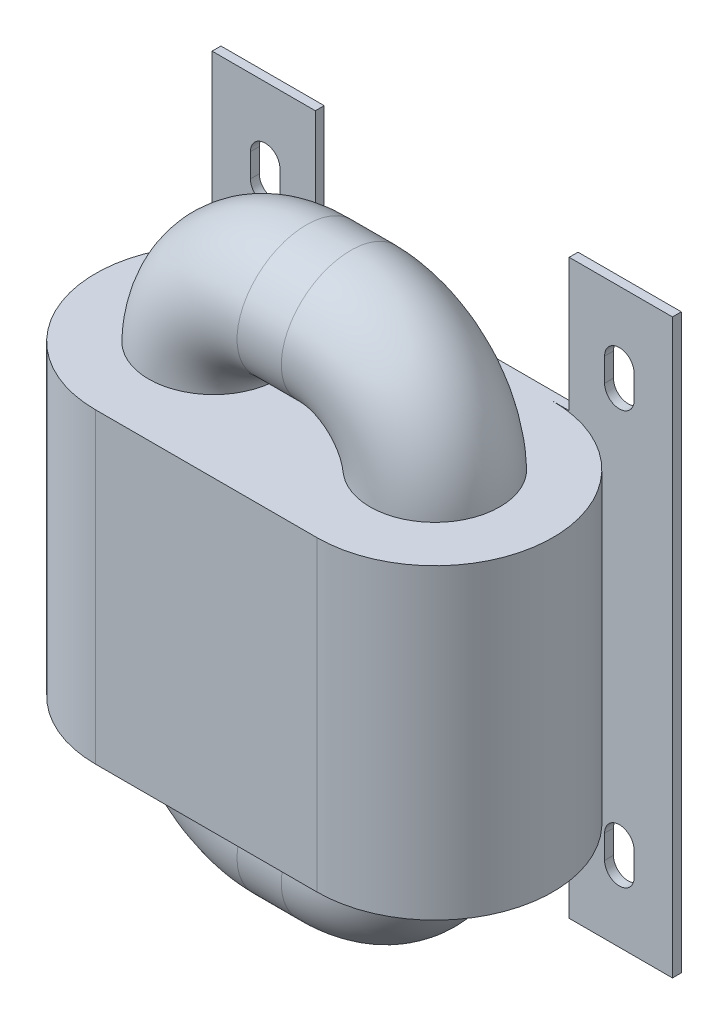
SolidWorks part; units mm, degrees
ref_plane "前视" through (0, 0, 0) normal (0, 0, 1) x (1, 0, 0)
ref_plane "上视" through (0, 0, 0) normal (0, 1, 0) x (1, 0, 0)
ref_plane "右视" through (0, 0, 0) normal (1, 0, 0) x (0, 0, -1)
sketch "草图1" plane through (0, 0, 0) normal (0, 1, 0) x (1, 0, 0)
  line L0 (0, 88.1369) -> (0, -92.5338) construction
  line L1 (-127.3089, 0) -> (111.3203, 0) construction
  line L2 (-18.75, 20) -> (18.75, 20)
  line L3 (-18.75, -20) -> (18.75, -20)
  arc A0 (-18.75, 20) -> (-18.75, -20) centre (-18.75, 0) ccw
  arc A1 (18.75, 20) -> (18.75, -20) centre (18.75, 0) cw
  dimension "D1" = 40
  dimension "D3" = 40
  dimension "D2" = 37.5
extrude "拉伸1" add sketch "草图1" along normal blind 52
sketch "草图2" plane through (0, 0, -20) normal (0, 0, -1) x (-1, 0, 0)
  line L0 (0, -24.0953) -> (0, 77.1566) construction
  line L1 (-65.697, 26) -> (66.5461, 26) construction
  line L2 (-18.75, 0) -> (18.75, 0) construction
  line L3 (39, 74.5) -> (39, -22.5)
  line L5 (-39, 74.5) -> (-39, -22.5)
  line L7 (-39, 74.5) -> (-21.5, 74.5)
  line L8 (-39, -22.5) -> (-21.5, -22.5)
  line L9 (-21.5, 0) -> (21.5, 0)
  line L10 (18.75, 0) -> (38.75, 0) construction
  line L11 (-21.5, 0) -> (-21.5, -22.5)
  line L12 (21.5, 0) -> (21.5, -22.5)
  line L13 (21.5, -22.5) -> (39, -22.5)
  line L14 (21.5, 52) -> (21.5, 74.5)
  line L15 (-21.5, 52) -> (-21.5, 74.5)
  line L16 (-21.5, 52) -> (21.5, 52)
  line L17 (21.5, 74.5) -> (39, 74.5)
  dimension "D1" = 26
  dimension "D2" = 97
  dimension "D3" = 78
  dimension "D4" = 43
extrude "拉伸2" add sketch "草图2" along normal blind 1.5
ref_plane "基准面1" through (0, 0, 0) normal (0, 0, 1) x (1, 0, 0)
sketch "草图3" plane through (0, 0, 0) normal (0, 0, 1) x (1, 0, 0)
  line L0 (0, 76.9957) -> (0, -34.1881) construction
  line L1 (18.75, 51) -> (18.75, 5)
  line L2 (-66.0355, 26) -> (65.5486, 26) construction
  line L3 (-18.75, 52) -> (18.75, 52) construction
  line L4 (-18.75, 51) -> (-18.75, 5)
  line L5 (-3.75, 66) -> (3.75, 66)
  line L6 (-3.75, -10) -> (3.75, -10)
  arc A0 (18.75, 51) -> (3.75, 66) centre (3.75, 51) ccw
  arc A1 (-18.75, 51) -> (-3.75, 66) centre (-3.75, 51) cw
  arc A2 (3.75, -10) -> (18.75, 5) centre (3.75, 5) ccw
  arc A3 (-3.75, -10) -> (-18.75, 5) centre (-3.75, 5) cw
  point P14 (18.75, 66)
  point P17 (-18.75, 66)
  point P20 (18.75, -10)
  point P23 (-18.75, -10)
  dimension "D5" = 15
  dimension "D6" = 15
  dimension "D1" = 76
  dimension "D2" = 26
  dimension "D3" = 40
  dimension "D4" = 37.5
sketch "草图4" plane through (0, 52, 0) normal (0, 1, 0) x (-1, 0, 0)
  circle A0 centre (-18.75, 0) radius 11
  dimension "D1" = 22
sweep "扫描4" add profiles "草图4" path "草图3"
sketch "草图6" plane through (0, 0, -21.5) normal (0, 0, -1) x (-1, 0, 0)
  line L0 (0, -25.2034) -> (0, 83.8054) construction
  line L2 (39, 26) -> (-39, 26) construction
  line L3 (39, -22.5) -> (39, 74.5) construction
  line L4 (-39, 74.5) -> (-39, -22.5) construction
  line L5 (-44.8519, 63) -> (54.6042, 63) construction
  line L6 (-44.8519, 59) -> (54.6042, 59) construction
  line L7 (-32.5, 63) -> (-32.5, 59)
  line L8 (-27.5, 63) -> (-27.5, 59)
  line L9 (-50.0274, 61) -> (61.9942, 61) construction
  line L10 (30, 83.8054) -> (30, -25.2034) construction
  line L11 (-30, 83.8054) -> (-30, -25.2034) construction
  line L12 (-50.0274, -9) -> (61.9942, -9) construction
  line L13 (32.5, 63) -> (32.5, 59)
  line L14 (27.5, 63) -> (27.5, 59)
  line L15 (32.5, -11) -> (32.5, -7)
  line L16 (27.5, -11) -> (27.5, -7)
  line L17 (-27.5, -11) -> (-27.5, -7)
  line L18 (-32.5, -11) -> (-32.5, -7)
  arc A0 (-32.5, 63) -> (-27.5, 63) centre (-30, 63) cw
  arc A1 (-32.5, 59) -> (-27.5, 59) centre (-30, 59) ccw
  arc A2 (32.5, 63) -> (27.5, 63) centre (30, 63) ccw
  arc A3 (32.5, 59) -> (27.5, 59) centre (30, 59) cw
  arc A4 (32.5, -7) -> (27.5, -7) centre (30, -7) ccw
  arc A5 (32.5, -11) -> (27.5, -11) centre (30, -11) cw
  arc A6 (-32.5, -11) -> (-27.5, -11) centre (-30, -11) ccw
  arc A7 (-32.5, -7) -> (-27.5, -7) centre (-30, -7) cw
  dimension "D7" = 2.5
  dimension "D1" = 35
  dimension "D2" = 70
  dimension "D3" = 60
  dimension "D4" = 30
  dimension "D5" = 4
  dimension "D6" = 2
extrude "切除-拉伸1" cut sketch "草图6" against normal blind 1.5
